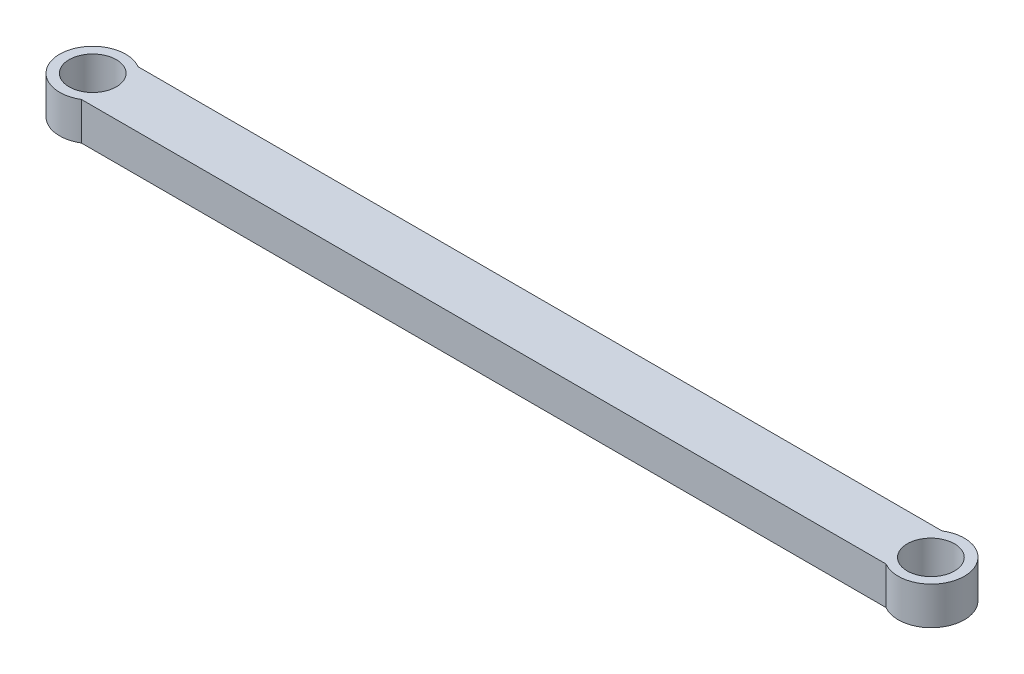
SolidWorks part; units mm, degrees
ref_plane "Front Plane" through (0, 0, 0) normal (0, 0, 1) x (1, 0, 0)
ref_plane "Top Plane" through (0, 0, 0) normal (0, 1, 0) x (1, 0, 0)
ref_plane "Right Plane" through (0, 0, 0) normal (1, 0, 0) x (0, 0, -1)
sketch "Sketch2" plane through (0, 0, 0) normal (0, 1, 0) x (1, 0, 0)
  line L0 (0, 1.75) -> (0, 1.25)
  line L1 (0, -1.25) -> (0, -1.75)
  line L2 (0, 1.5) -> (44.3835, 1.5)
  line L3 (0, -1.5) -> (44.3835, -1.5)
  line L4 (44.3835, 1.7605) -> (44.3835, 1.2395)
  line L5 (44.3835, -1.2605) -> (44.3835, -1.7395)
  circle A0 centre (0, 0) radius 1.75
  circle A1 centre (0, 0) radius 1.25
  circle A2 centre (44.3835, 0.0105) radius 1.75
  circle A3 centre (44.3835, -0.0105) radius 1.25
  point P22 (44.3835, 1.5)
  dimension "D1" = 3.5
  dimension "D3" = 3.5
  dimension "D2" = 0.5
extrude "Boss-Extrude1" add sketch "Sketch2" along normal blind 2 contours A2 L2 A0 L3 | A1 L1 L3 A0 L2 L0 | A1 L0 A0 L1 | A3 L5 A2 L4 | A3 L4 L2 A2 L3 L5 | L2 A0 L0 | L1 A0 L3 | L4 A2 L2 | L3 A2 L5
sketch "Sketch3" plane through (0, 2, 0) normal (0, 1, 0) x (1, 0, 0)
  circle A0 centre (44.3835, -0.0105) radius 1.25
  circle A1 centre (0, 0) radius 1.25
  dimension "D1" = 2.5
  dimension "D2" = 2.5
